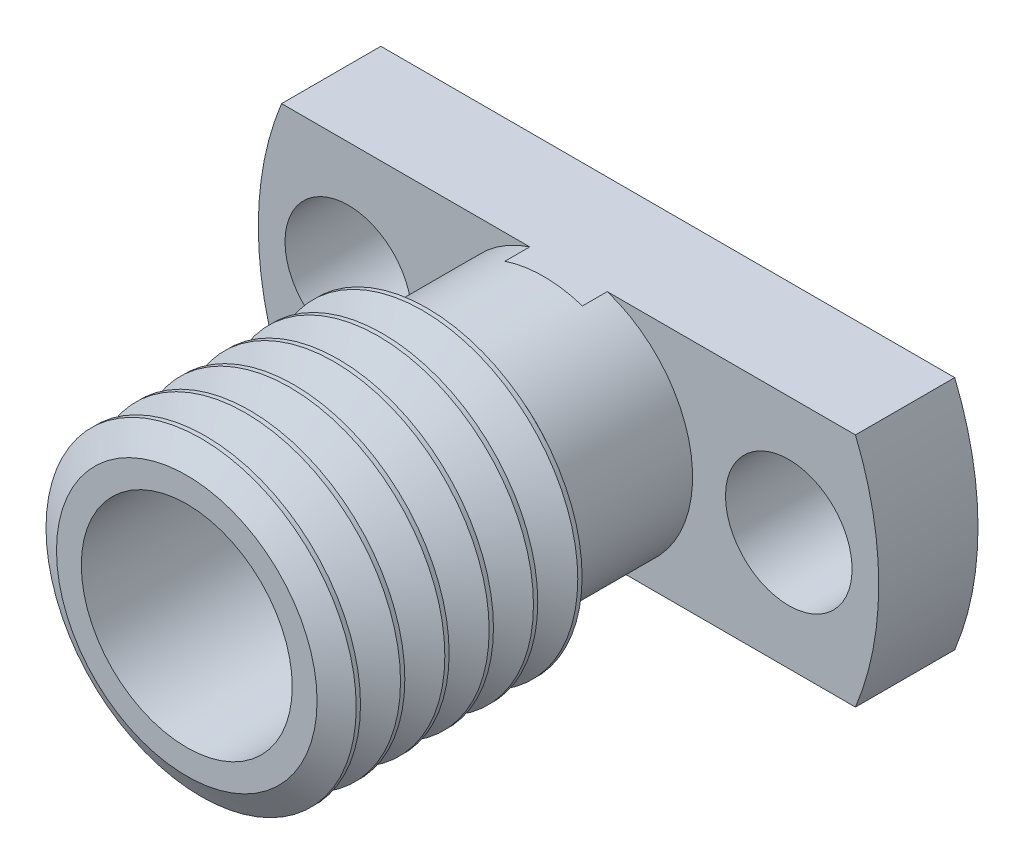
SolidWorks part; units mm, degrees
material "ASTM A36 Steel"
ref_plane "Front Plane" through (0, 0, 0) normal (0, 0, 1) x (1, 0, 0)
ref_plane "Top Plane" through (0, 0, 0) normal (0, 1, 0) x (1, 0, 0)
ref_plane "Right Plane" through (0, 0, 0) normal (1, 0, 0) x (0, 0, -1)
ref_axis "Axis1" through (0, 0, -0.4923) along (0, 0, 1)
sketch "Sketch1" plane through (0, 0, 0) normal (1, 0, 0) x (0, 0, -1)
  line L0 (-2.032, 2.54) -> (-4.5124, 2.54)
  line L1 (-4.5124, 2.54) -> (-4.879, 3.175)
  line L2 (-4.879, 3.175) -> (-9.5531, 3.175)
  line L3 (-2.032, 2.54) -> (-2.032, 8.255)
  line L4 (-2.032, 8.255) -> (0, 8.255)
  line L5 (0, 8.255) -> (0, 0.762)
  line L6 (-9.5237, 3.2766) -> (-9.0555, 2.4656) construction
  line L7 (-9.5531, 3.175) -> (-9.8464, 2.667)
  line L8 (-6.7939, 0) -> (-3.1004, 0) construction
  line L9 (-9.8464, 2.667) -> (-9.8464, 2.159)
  line L10 (-9.8464, 2.159) -> (-6.7939, 2.159)
  line L11 (-6.7939, 2.159) -> (-6.7939, 1.524)
  line L12 (-6.7939, 1.524) -> (-3.1004, 1.524)
  line L13 (-3.1004, 1.524) -> (-3.1004, 0.762)
  line L14 (-3.1004, 0.762) -> (0, 0.762)
  line L15 (-9.0555, 2.4656) -> (-8.5873, 3.2766) construction
  line L16 (-8.5873, 3.2766) -> (-9.5237, 3.2766) construction
  point P9 (-8.6459, 3.175)
  dimension "D1" = 16.51
  dimension "D2" = 9.8464
  dimension "D3" = 2.032
  dimension "D4" = 3.0525
  dimension "D5" = 6.746
  dimension "D6" = 1.524
  dimension "D7" = 3.048
  dimension "D8" = 4.318
  dimension "D9" = 6.35
  dimension "D10" = 5.08
  dimension "D11" = 5.334
  dimension "D12" = 60
  dimension "D13" = 60
  dimension "D14" = 0.508
  dimension "D15" = 0.9071
  dimension "D16" = 0.1016
  dimension "D17" = 0.0762
revolve "Revolve1" add sketch "Sketch1" angle 360 about L8
sketch "Sketch5" plane through (0, 0, 0) normal (0, 0, 1) x (1, 0, 0)
  line L0 (5.8737, -2.413) -> (-5.8737, -2.413)
  line L1 (5.8737, 2.413) -> (-5.8737, 2.413)
  line L2 (0, -2.9619) -> (0, -5.6187) construction
  arc A0 (-5.8737, -2.413) -> (-5.8737, 2.413) centre (0, 0) cw
  circle A1 centre (-4.5085, 0) radius 1.2954
  circle A2 centre (4.5085, 0) radius 1.2954
  arc A3 (5.8737, -2.413) -> (5.8737, 2.413) centre (0, 0) ccw
  point P9 (-6.35, 0)
  dimension "D1" = 6.35
  dimension "D3" = 2.5908
  dimension "D2" = 4.826
  dimension "D4" = 9.017
extrude "CE-00 500 355" cut sketch "Sketch5" along normal blind 2.54 flip side to cut
sketch "Sketch7" [suppressed] plane through (0, 0, 0) normal (0, 0, 1) x (1, 0, 0)
  line L0 (-6.555, 2.413) -> (6.555, 2.413)
  line L1 (-6.555, -2.413) -> (6.555, -2.413)
  line L2 (0, 2.2064) -> (0, 6.4893) construction
  circle A0 centre (-5.08, 0) radius 1.2954
  arc A1 (-6.555, -2.413) -> (-6.555, 2.413) centre (0, 0) cw
  circle A2 centre (5.08, 0) radius 1.2954
  arc A3 (6.555, -2.413) -> (6.555, 2.413) centre (0, 0) ccw
  point P6 (-6.985, 0)
  dimension "D1" = 2.5908
  dimension "D2" = 13.97
  dimension "D3" = 4.826
  dimension "D4" = 10.16
extrude "CE-00 550 400" [suppressed] cut sketch "Sketch7" along normal blind 2.54 flip side to cut
sketch "Sketch2" plane through (0, 0, 0) normal (0, 0, 1) x (1, 0, 0)
  line L0 (0, -3.3515) -> (0, -5.9934) construction
  line L1 (-6.1482, 2.8321) -> (6.1482, 2.8321)
  line L2 (-7.9375, 1.0428) -> (-7.9375, -1.0428)
  line L3 (-6.1482, -2.8321) -> (6.1482, -2.8321)
  line L4 (7.9375, -1.0428) -> (6.1482, -2.8321)
  line L5 (-7.9375, 1.0428) -> (-6.1482, 2.8321)
  line L6 (-7.9375, -1.0428) -> (-6.1482, -2.8321)
  line L7 (7.9375, 1.0428) -> (6.1482, 2.8321)
  line L8 (7.9375, 1.0428) -> (7.9375, -1.0428)
  circle A0 centre (-6.1087, 0) radius 1.2954
  circle A1 centre (6.1087, 0) radius 1.2954
  point P4 (-7.9375, 0)
  point P14 (7.9375, 0)
  dimension "D2" = 2.5908
  dimension "D1" = 5.6642
  dimension "D3" = 12.2174
  dimension "D4" = 15.875
  dimension "D5" = 45
  dimension "D7" = 6.35
extrude "CE-00 625 481" [suppressed] cut sketch "Sketch2" along normal blind 2.54 flip side to cut
sketch "Sketch6" [suppressed] plane through (0, 0, 0) normal (0, 0, 1) x (1, 0, 0)
  line L0 (0, 3.072) -> (0, 4.8919) construction
  line L1 (-4.1857, 4.7752) -> (4.1857, 4.7752)
  line L2 (-4.7625, 4.2001) -> (-4.7625, -4.2001)
  line L3 (-4.1857, -4.7752) -> (4.1857, -4.7752)
  line L4 (4.7625, 4.2001) -> (4.7625, -4.2001)
  arc A0 (-4.1857, -4.7752) -> (-4.7625, -4.2001) centre (0, 0) cw
  arc A1 (-4.7625, 4.2001) -> (-4.1857, 4.7752) centre (0, 0) cw
  arc A2 (4.7625, 4.2001) -> (4.1857, 4.7752) centre (0, 0) ccw
  arc A3 (4.1857, -4.7752) -> (4.7625, -4.2001) centre (0, 0) ccw
  circle A4 centre (-3.175, 3.175) radius 0.8255
  circle A5 centre (-3.175, -3.175) radius 0.8255
  circle A6 centre (3.175, 3.175) radius 0.8255
  circle A7 centre (3.175, -3.175) radius 0.8255
  dimension "D4" = 6.35
  dimension "D8" = 1.651
  dimension "D1" = 4.7752
  dimension "D2" = 4.7752
  dimension "D3" = 9.525
  dimension "D5" = 3.175
  dimension "D6" = 3.175
  dimension "D7" = 6.35
extrude "Cut-Extrude1" [suppressed] cut sketch "Sketch6" along normal blind 2.54 flip side to cut
sketch "Sketch4" plane through (0, 0, 0) normal (1, 0, 0) x (0, 0, -1)
  line L0 (-9.5237, 3.2766) -> (-9.0555, 2.4656) construction
  line L1 (-8.5873, 3.2766) -> (-9.5237, 3.2766) construction
  line L2 (-9.0555, 2.4656) -> (-8.5873, 3.2766) construction
  line L3 (-9.5237, 3.2766) -> (-9.0555, 2.4656)
  line L4 (-8.5873, 3.2766) -> (-9.5237, 3.2766)
  line L5 (-9.0555, 2.4656) -> (-8.5873, 3.2766)
revolve "Cut-Revolve1" cut sketch "Sketch4" angle 360 about axis through (0, 0, -0.4923) along (0, 0, 1)
pattern_linear "LPattern4" count 6 spacing 0.9071 along (0, 0, -1) of "Cut-Revolve1"
